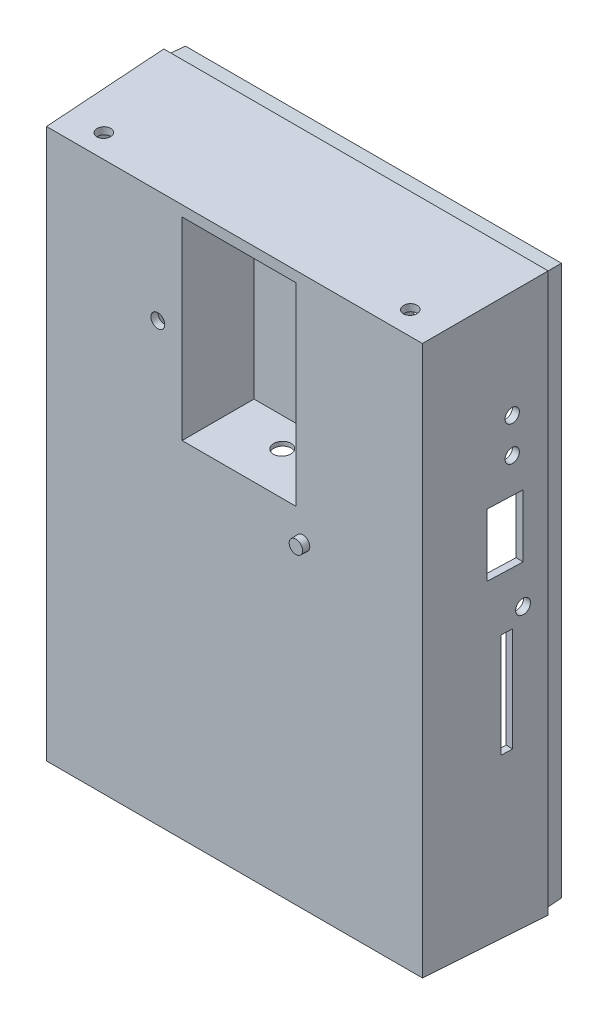
SolidWorks part; units mm, degrees
ref_plane "Front Plane" through (0, 0, 0) normal (0, 0, 1) x (1, 0, 0)
ref_plane "Top Plane" through (0, 0, 0) normal (0, 1, 0) x (1, 0, 0)
ref_plane "Right Plane" through (0, 0, 0) normal (1, 0, 0) x (0, 0, -1)
sketch "Sketch1" plane through (-178.9356, -87.8276, -1672.8765) normal (0, 0, 1) x (1, 0, 0)
  line L0 (27.3099, 6.0084) -> (138.0083, 6.0084) construction
  line L1 (138.0083, 6.0084) -> (138.0083, 166.7068) construction
  line L2 (138.0083, 166.7068) -> (27.3099, 166.7068) construction
  line L3 (27.3099, 166.7068) -> (27.3099, 6.0084) construction
  line L4 (27.3099, 6.0084) -> (138.0083, 6.0084)
  line L5 (138.0083, 6.0084) -> (138.0083, 166.7068)
  line L6 (138.0083, 166.7068) -> (27.3099, 166.7068)
  line L7 (27.3099, 166.7068) -> (27.3099, 6.0084)
extrude "Boss-Extrude1" add sketch "Sketch1" along normal blind 35 draft 2
shell "Shell1" thickness 2
sketch "Sketch9" plane through (0, 0, -1639.8765) normal (0, 0, -1) x (-1, 0, 0)
  line L0 (44.081, 75.7256) -> (148.4722, 75.7256) construction
  line L1 (77.4722, 75.7256) -> (112.4722, 75.7256)
  line L2 (77.4722, 75.7256) -> (77.4722, 17.7256)
  line L3 (77.4722, 17.7256) -> (112.4722, 17.7256)
  line L4 (112.4722, 75.7256) -> (112.4722, 17.7256)
  line L5 (148.4722, 75.7256) -> (148.4722, -78.6656) construction
  dimension "D1" = 58
  dimension "D2" = 35
  dimension "D3" = 36
extrude "Boss-Extrude5" add sketch "Sketch9" along normal blind 32 draft 2
sketch "Sketch6" plane through (-99.2245, 0, -3.465) normal (0.9994, 0, 0.0349) x (0.0349, 0, -0.9994)
  line L0 (1635.4078, -80.597) -> (1635.4078, 77.657) construction
  line L1 (1657.3178, -35.597) -> (1660.5178, -35.597)
  line L2 (1657.3178, -35.597) -> (1657.3178, -5.597)
  line L3 (1657.3178, -5.597) -> (1660.5178, -5.597)
  line L4 (1660.5178, -35.597) -> (1660.5178, -5.597)
  line L5 (1657.3178, -35.597) -> (1660.5178, -5.597) construction
  line L6 (1657.3178, -5.597) -> (1660.5178, -35.597) construction
  point P0 (1658.9178, -20.597)
  dimension "D1" = 30
  dimension "D2" = 3.2
  dimension "D3" = 45
  dimension "D4" = 23.51
extrude "Cut-Extrude3" cut sketch "Sketch6" against normal up to next (2 mm away) draft 2 draft outward yes
sketch "Sketch11" plane through (0, 0, -1637.8765) normal (0, 0, 1) x (1, 0, 0)
  line L1 (-111.3547, 74.6081) -> (-78.5896, 74.6081)
  line L2 (-111.3547, 74.6081) -> (-111.3547, 18.8431)
  line L3 (-111.3547, 18.8431) -> (-78.5896, 18.8431)
  line L4 (-78.5896, 74.6081) -> (-78.5896, 18.8431)
extrude "Cut-Extrude4" cut sketch "Sketch11" against normal blind 20 draft 2
sketch "Sketch13" plane through (0, -39.492, -1.3791) normal (0, -0.9994, -0.0349) x (1, 0, 0)
  line L0 (-77.4722, -1639.4962) -> (-112.4722, -1639.4962) construction
  circle A0 centre (-94.4722, -1649.4962) radius 2.5
  dimension "D1" = 5
  dimension "D2" = 10
  dimension "D3" = 17
extrude "Cut-Extrude5" cut sketch "Sketch13" against normal up to next (1.1866 mm away) draft 2 draft outward yes
sketch "Sketch14" plane through (0, 0, -1639.8765) normal (0, 0, -1) x (-1, 0, 0)
  line L0 (59.0793, -3.6656) -> (119.0793, -3.6656) construction
  line L1 (119.0793, -3.6656) -> (119.0793, -43.6656) construction
  line L2 (119.0793, -43.6656) -> (59.0793, -43.6656) construction
  line L3 (59.0793, -3.6656) -> (59.0793, -43.6656) construction
  line L4 (148.4722, -78.6656) -> (44.081, -78.6656) construction
  line L5 (44.081, -78.6656) -> (44.081, 75.7256) construction
  circle A0 centre (59.0793, -3.6656) radius 4
  circle A1 centre (59.0793, -43.6656) radius 4
  circle A2 centre (119.0793, -3.6656) radius 4
  circle A3 centre (119.0793, -43.6656) radius 4
  dimension "D1" = 8
  dimension "D2" = 8
  dimension "D3" = 8
  dimension "D4" = 8
  dimension "D5" = 60
  dimension "D6" = 40
  dimension "D7" = 35
  dimension "D8" = 14.9983
extrude "Boss-Extrude6" add sketch "Sketch14" along normal blind 18 draft 2
sketch "Sketch15" plane through (0, 0, -1657.8765) normal (0, 0, -1) x (-1, 0, 0)
  circle A0 centre (59.0793, -3.6656) radius 2
  circle A1 centre (119.0793, -3.6656) radius 2
  circle A2 centre (119.0793, -43.6656) radius 2
  circle A3 centre (59.0793, -43.6656) radius 2
  dimension "D1" = 4
  dimension "D2" = 4
  dimension "D3" = 4
  dimension "D4" = 4
extrude "Cut-Extrude6" cut sketch "Sketch15" against normal blind 5 draft 2
sketch "Sketch17" plane through (0, 0, -1672.8765) normal (0, 0, -1) x (-1, 0, 0)
  line L0 (149.6246, -79.818) -> (42.9286, -79.818) construction
  line L1 (149.6246, 76.878) -> (149.6246, -79.818) construction
  line L2 (42.9286, -79.818) -> (42.9286, 76.878) construction
  line L3 (42.9286, 76.878) -> (149.6246, 76.878) construction
  line L4 (149.6246, -79.818) -> (42.9286, -79.818)
  line L5 (149.6246, 76.878) -> (149.6246, -79.818)
  line L6 (42.9286, -79.818) -> (42.9286, 76.878)
  line L7 (42.9286, 76.878) -> (149.6246, 76.878)
  line L8 (41.9286, 77.878) -> (150.6246, 77.878)
  line L9 (150.6246, 77.878) -> (150.6246, -80.818)
  line L10 (150.6246, -80.818) -> (41.9286, -80.818)
  line L11 (41.9286, -80.818) -> (41.9286, 77.878)
  dimension "D1" = 1
extrude "Boss-Extrude8" add sketch "Sketch17" along normal blind 5 draft 2
sketch "Sketch18" plane through (0, 0, -1637.8765) normal (0, 0, 1) x (1, 0, 0)
  line L0 (-111.3547, 18.8431) -> (-78.5896, 18.8431) construction
  line L1 (-78.5896, 18.8431) -> (-78.5896, 74.6081) construction
  circle A0 centre (-76.5896, 10.7256) radius 2
  dimension "D1" = 4
  dimension "D2" = 8.1175
  dimension "D3" = 2
extrude "Boss-Extrude9" add sketch "Sketch18" along normal blind 2 draft 2
sketch "Sketch19" plane through (0, 0, -1637.8765) normal (0, 0, 1) x (1, 0, 0)
  line L0 (-111.3547, 18.8431) -> (-78.5896, 18.8431) construction
  line L1 (-111.3547, 74.6081) -> (-111.3547, 18.8431) construction
  circle A0 centre (-118.3547, 45.2431) radius 2
  dimension "D1" = 4
  dimension "D2" = 26.4
  dimension "D3" = 7
extrude "Cut-Extrude7" cut sketch "Sketch19" against normal up to next (2 mm away) draft 2
sketch "Sketch26" plane through (-91.0953, 0, 3.1811) normal (0.9994, 0, -0.0349) x (-0.0349, 0, -0.9994)
  circle A1 centre (1670.1491, -1.47) radius 2
  circle A2 centre (1670.1491, -1.47) radius 2
  dimension "D1" = 0
extrude "Cut-Extrude11" cut sketch "Sketch26" against normal up to next (2 mm away) draft 2 draft outward yes
sketch "Sketch27" plane through (-101.2233, 0, -3.5348) normal (-0.9994, 0, -0.0349) x (-0.0349, 0, 0.9994)
  circle A1 centre (-1663.4291, -1.47) radius 2
  circle A2 centre (-1663.4291, -1.47) radius 2
  dimension "D1" = 0
extrude "Cut-Extrude12" cut sketch "Sketch27" against normal up to next (2 mm away) draft 2 draft outward yes
sketch "Sketch29" plane through (-93.0941, 0, 3.2509) normal (-0.9994, 0, 0.0349) x (0.0349, 0, 0.9994)
  line L0 (-1677.1491, 78.8792) -> (-1677.1491, -81.8192) construction
  circle A0 centre (-1662.1491, -30.597) radius 6
  dimension "D2" = 12
  dimension "D1" = 15
  dimension "D3" = 50
extrude "Cut-Extrude15" cut sketch "Sketch29" against normal blind 10 draft 2 draft outward yes
sketch "Sketch32" plane through (-99.2245, 0, -3.465) normal (0.9994, 0, 0.0349) x (0.0349, 0, -0.9994)
  line L0 (1670.4291, -81.8192) -> (1670.4291, 78.8792) construction
  line L1 (1663.4291, 9.657) -> (1653.4291, 9.657)
  line L2 (1663.4291, 9.657) -> (1663.4291, 27.657)
  line L3 (1663.4291, 27.657) -> (1653.4291, 27.657)
  line L4 (1653.4291, 9.657) -> (1653.4291, 27.657)
  line L5 (1663.4291, 9.657) -> (1653.4291, 27.657) construction
  line L6 (1663.4291, 27.657) -> (1653.4291, 9.657) construction
  line L8 (1660.4078, 47.657) -> (1660.4078, 37.657) construction
  line L9 (1635.4078, -80.597) -> (1635.4078, 77.657) construction
  circle A0 centre (1660.4078, 47.657) radius 2
  circle A1 centre (1660.4078, 37.657) radius 2
  point P0 (1658.4291, 18.657)
  dimension "D5" = 4
  dimension "D6" = 4
  dimension "D1" = 10
  dimension "D2" = 18
  dimension "D3" = 12
  dimension "D4" = 59
  dimension "D7" = 10
  dimension "D8" = 30
  dimension "D9" = 25
extrude "Cut-Extrude16" cut sketch "Sketch32" against normal up to next (2 mm away) draft 2
sketch "Sketch34" plane through (0, 20.4361, 0.7136) normal (0, 0.9994, 0.0349) x (1, 0, 0)
  line L0 (-42.1496, 1639.5889) -> (-150.4035, 1639.5889) construction
  circle A0 centre (-140.4035, 1646.0889) radius 2
  circle A1 centre (-52.1496, 1646.0889) radius 2
  dimension "D1" = 4
  dimension "D2" = 4
  dimension "D3" = 6.5
  dimension "D4" = 6.5
  dimension "D5" = 10
  dimension "D6" = 10
extrude "Cut-Extrude17" cut sketch "Sketch34" against normal up to next (2 mm away) draft 2
scale "Scale1"
other "Parting Line2"
other "Parting Surface2" parameters "D1"=50
sketch "Sketch28" plane through (0, 0, -1682.7469) normal (0, 0, 1) x (1, 0, 0)
  line L1 (17.5531, 131.7307) -> (-209.2065, 131.7307)
  line L2 (17.5531, 131.7307) -> (17.5531, -148.2693)
  line L3 (17.5531, -148.2693) -> (-209.2065, -148.2693)
  line L4 (-209.2065, 131.7307) -> (-209.2065, -148.2693)
  line L5 (17.5531, 131.7307) -> (-209.2065, -148.2693) construction
  line L6 (17.5531, -148.2693) -> (-209.2065, 131.7307) construction
  point P0 (-95.8267, -8.2693)
  dimension "D1" = 280
  dimension "D2" = 226.7596
  dimension "D3" = 17.5531
  dimension "D4" = 131.7307
